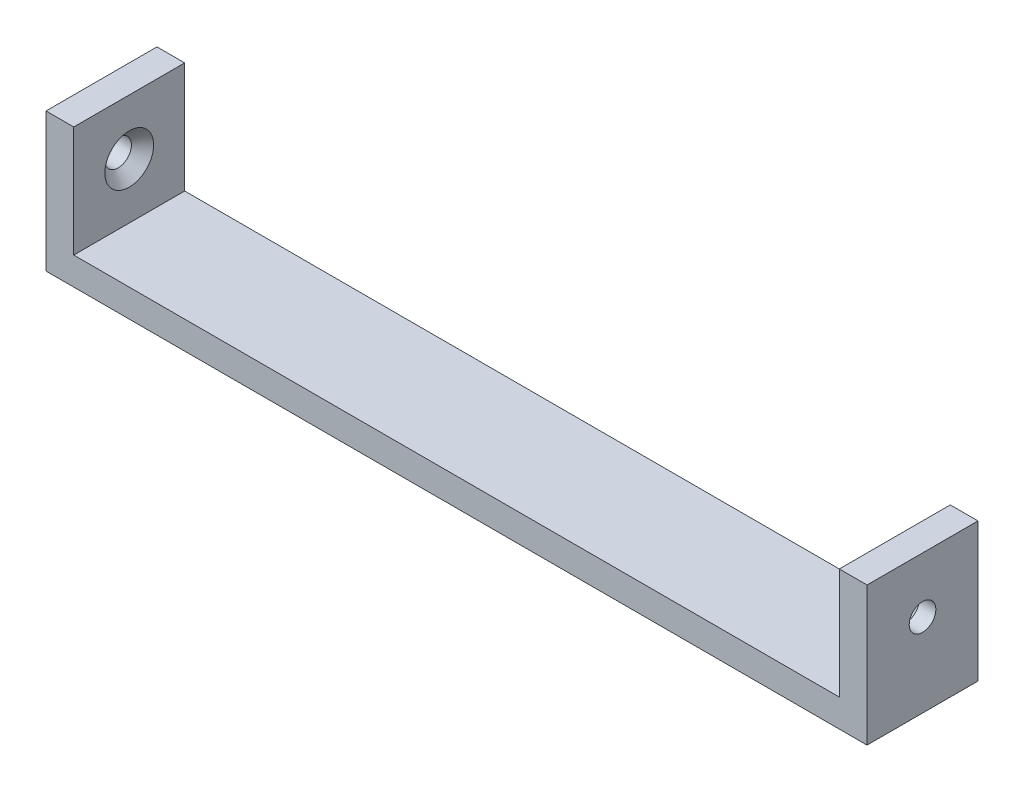
SolidWorks part; units mm, degrees
ref_plane "Front Plane" through (0, 0, 0) normal (0, 0, 1) x (1, 0, 0)
ref_plane "Top Plane" through (0, 0, 0) normal (0, 1, 0) x (1, 0, 0)
ref_plane "Right Plane" through (0, 0, 0) normal (1, 0, 0) x (0, 0, -1)
sketch "Sketch2" plane through (0, 0, 0) normal (0, 1, 0) x (1, 0, 0)
  line L1 (-11.6417, 5.692) -> (62.3583, 5.692)
  line L2 (-11.6417, 5.692) -> (-11.6417, -4.308)
  line L3 (-11.6417, -4.308) -> (62.3583, -4.308)
  line L4 (62.3583, 5.692) -> (62.3583, -4.308)
  dimension "D1" = 10
  dimension "D2" = 74
extrude "Boss-Extrude1" add sketch "Sketch2" along normal blind 2.5 contours L1 L4 L3 L2
sketch "Sketch3" plane through (0, 2.5, 0) normal (0, 1, 0) x (1, 0, 0)
  line L2 (-9.1417, 5.692) -> (-9.1417, -4.308)
  line L3 (-9.1417, 5.692) -> (-9.1417, -4.308) construction
  line L5 (59.8583, 5.692) -> (59.8583, -4.308)
  line L6 (59.8583, 5.692) -> (59.8583, -4.308) construction
  line L7 (-11.6417, 5.692) -> (-9.1417, 5.692)
  line L8 (-11.6417, 5.692) -> (-11.6417, -4.308)
  line L9 (-11.6417, -4.308) -> (-9.1417, -4.308)
  line L10 (-9.1417, 5.692) -> (-9.1417, -4.308)
  line L11 (59.8583, 5.692) -> (62.3583, 5.692)
  line L12 (59.8583, 5.692) -> (59.8583, -4.308)
  line L13 (59.8583, -4.308) -> (62.3583, -4.308)
  line L14 (62.3583, 5.692) -> (62.3583, -4.308)
  dimension "D1" = 2.5
  dimension "D2" = 2.5
extrude "Boss-Extrude2" add sketch "Sketch3" along normal blind 10
hole_wizard "CSK for M2 Flat Head Machine Screw1" positions "Sketch4" profile "Sketch5" countersink size "M2" standard "ANSI Metric"
sketch "Sketch4" plane through (59.8583, 0, 0) normal (-1, 0, 0) x (0, 0, 1)
  line L0 (4.308, 12.5) -> (4.308, 2.5) construction
  line L1 (-5.692, 12.5) -> (4.308, 12.5) construction
  point P0 (-0.692, 7.5)
  dimension "D1" = 5
  dimension "D2" = 5
sketch "Sketch5" plane through (59.8583, 7.5, -0.692) normal (0, 1, 0) x (0, 0, 1)
  line L0 (0, 0) -> (0, 2.5)
  line L1 (0, 2.5) -> (1.2, 2.5)
  line L2 (1.2, 2.5) -> (1.2, 1)
  line L3 (1.2, 1) -> (2.2, 0)
  line L5 (2.2, 0) -> (0, 0)
  line L6 (-1.2, 1) -> (-2.2, 0) construction
  line L11 (0, -6.35) -> (0, 107.95) construction
  dimension "Thru Hole Dia." = 2.4
  dimension "Thru Hole Depth" = 2.5
  dimension "Near C'Sink Dia." = 4.4
  dimension "Near C'Sink Angle" = 90
hole_wizard "CSK for M2 Flat Head Machine Screw2" positions "Sketch6" profile "Sketch7" countersink size "M2" standard "ANSI Metric"
sketch "Sketch6" plane through (-9.1417, 0, 0) normal (1, 0, 0) x (0, 0, -1)
  line L0 (5.692, 12.5) -> (5.692, 2.5) construction
  line L2 (-4.308, 2.5) -> (5.692, 2.5) construction
  point P0 (0.692, 7.5)
  point P9 (-0.2783, 2.5)
  dimension "D1" = 5
  dimension "D2" = 5
sketch "Sketch7" plane through (-9.1417, 7.5, -0.692) normal (0, 1, 0) x (0, 0, -1)
  line L0 (0, 0) -> (0, 2.5)
  line L1 (0, 2.5) -> (1.2, 2.5)
  line L2 (1.2, 2.5) -> (1.2, 1)
  line L3 (1.2, 1) -> (2.2, 0)
  line L5 (2.2, 0) -> (0, 0)
  line L6 (-1.2, 1) -> (-2.2, 0) construction
  line L11 (0, -6.35) -> (0, 107.95) construction
  dimension "Thru Hole Dia." = 2.4
  dimension "Thru Hole Depth" = 2.5
  dimension "Near C'Sink Dia." = 4.4
  dimension "Near C'Sink Angle" = 90
